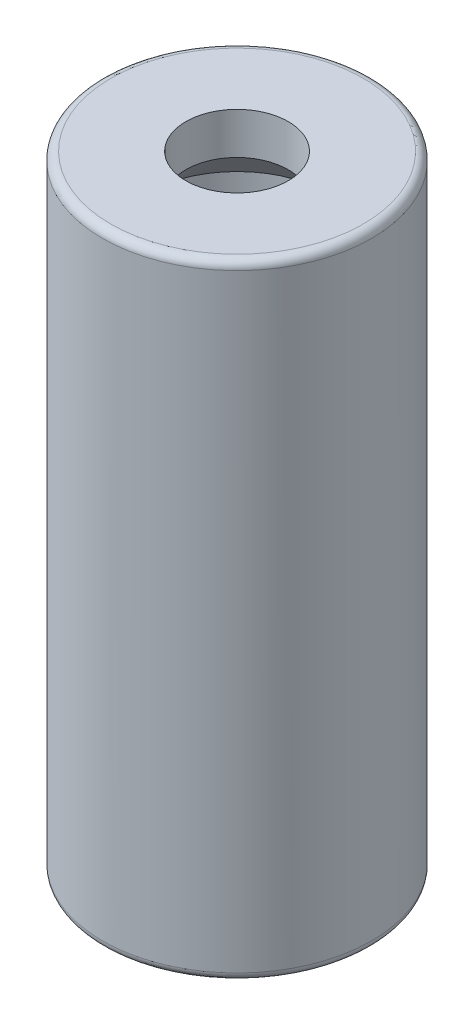
SolidWorks part; units mm, degrees
ref_plane "Front" through (0, 0, 0) normal (0, 0, 1) x (1, 0, 0)
ref_plane "Top" through (0, 0, 0) normal (0, 1, 0) x (1, 0, 0)
ref_plane "Right" through (0, 0, 0) normal (1, 0, 0) x (0, 0, -1)
sketch "Sketch1" plane through (0, 0, 0) normal (0, 1, 0) x (1, 0, 0)
  circle A0 centre (0, 0) radius 16.15
  circle A1 centre (0, 0) radius 11.15
  dimension "D1" = 32.3
  dimension "D2" = 5
extrude "Boss-Extrude1" add sketch "Sketch1" along normal blind 60
sketch "Sketch2" plane through (0, 0, 0) normal (0, -1, 0) x (1, 0, 0)
  circle A1 centre (0, 0) radius 16.15 construction
  circle A2 centre (0, 0) radius 16.15
extrude "Boss-Extrude2" add sketch "Sketch2" along normal blind 5
sketch "Sketch3" plane through (0, 0, 0) normal (0, 0, 1) x (1, 0, 0)
  line L0 (0, 60) -> (0, -5) construction
  line L1 (11.15, 60) -> (-11.15, 60) construction
  line L2 (-16.15, -5) -> (16.15, -5) construction
  line L3 (-11.15, 60) -> (-6.15, 65)
  line L4 (16.15, 60) -> (-16.15, 60) construction
  line L5 (-6.15, 65) -> (-6.15, 70)
  line L6 (-6.15, 70) -> (-16.15, 70)
  line L7 (-16.15, 70) -> (-16.15, 60)
  line L8 (-16.15, 60) -> (-11.15, 60)
  dimension "D1" = 10
  dimension "D2" = 10
  dimension "D3" = 5
revolve "Revolve1" add sketch "Sketch3" angle 360 about L0
fillet "Fillet1" radius 1 2 edges at (0, 70, 16.15) (0, -5, -16.15)
